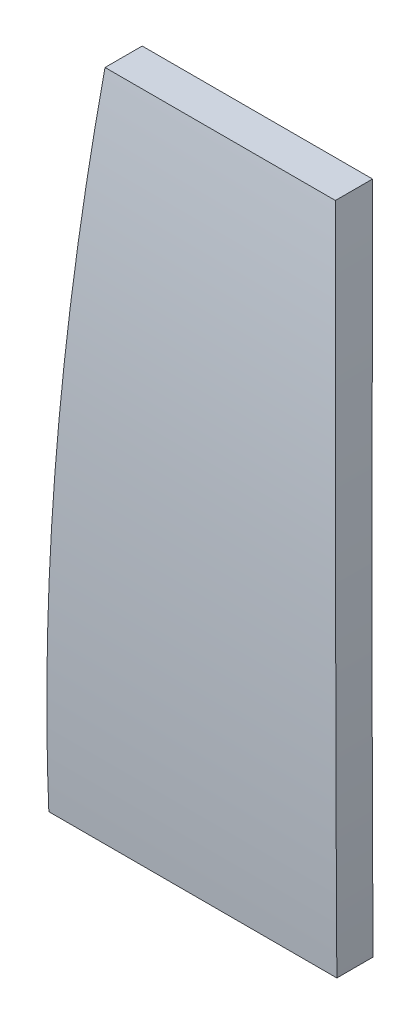
SolidWorks part; units mm, degrees
material "Glass"
ref_plane "Front Plane" through (0, 0, 0) normal (0, 0, 1) x (1, 0, 0)
ref_plane "Top Plane" through (0, 0, 0) normal (0, 1, 0) x (1, 0, 0)
ref_plane "Right Plane" through (0, 0, 0) normal (1, 0, 0) x (0, 0, -1)
sketch "Sketch1" plane through (0, 0, 0) normal (0, 0, 1) x (1, 0, 0)
  line L0 (0, 1295.4) -> (484.0694, 1295.4)
  line L1 (0, 1295.4) -> (0, 0)
  line L2 (0, 0) -> (605.2535, 0)
  arc A0 (484.0694, 1295.4) -> (605.2535, 0) centre (-4462.9365, 179.2413) cw
  dimension "D1" = 5071.3585
  dimension "D2" = 484.0694
  dimension "D3" = 1295.4
  dimension "D4" = 605.2535
extrude "Boss-Extrude1" add sketch "Sketch1" along normal mid plane 508
sketch "Sketch2" plane through (0, 0, 0) normal (1, 0, 0) x (0, 0, -1)
  line L1 (118.0703, 1295.4) -> (-254, 1295.4)
  line L3 (-254, 1295.4) -> (-254, 0)
  line L4 (-254, 0) -> (0, 0)
  line L5 (196.1868, 1295.4) -> (254, 1295.4)
  line L7 (0, 0) -> (76.2672, 0)
  line L8 (196.1868, 1295.4) -> (118.0703, 1295.4)
  line L10 (254, 1295.4) -> (254, 0)
  line L11 (254, 0) -> (76.2672, 0)
  spline S4 degree 3 poles (118.0703, 1295.4) (94.5648, 1190.445) (74.2845, 1084.7664) (40.4506, 871.8984) (26.8971, 764.7092) (6.8137, 548.7534) (0.2837, 439.9866) (-3.2892, 302.9971) (-3.7742, 275.5476) (-4.1536, 234.2952) (-4.2562, 213.6494) (-4.2275, 192.9741) (-4.1791, 179.184) (-4.1402, 172.2852) (-3.659, 110.214) (-2.2952, 55.0846) (0, 0) knots 0 0 0 0 0.25 0.25 0.5 0.5 0.75 0.75 0.8125 0.8125 0.84375 0.859375 0.859375 0.875 0.875 1 1 1 1
  spline S5 degree 3 poles (76.2672, 0) (75.1005, 27.5617) (73.7059, 68.9228) (72.7021, 117.2098) (72.4057, 137.9111) (72.2378, 151.7136) (72.1687, 158.6169) (71.6812, 220.7208) (72.2017, 275.7138) (76.5602, 440.0755) (83.1946, 548.8269) (103.5954, 764.7556) (117.362, 871.933) (151.7238, 1084.781) (172.319, 1190.4514) (196.1868, 1295.4) knots 0 0 0 0 0.0625 0.09375 0.109375 0.109375 0.125 0.125 0.25 0.25 0.5 0.5 0.75 0.75 1 1 1 1
extrude "Cut-Extrude1" cut sketch "Sketch2" along normal through all contours S4 L1 L3 L4 | S5 L11 L10 L5
ref_plane "Plane1" through (-2.54, 0, 0) normal (-1, 0, 0) x (0, 0, 1)
ref_plane "Plane2" through (608.4221, 0, 0) normal (1, 0, 0) x (0, 0, -1)
